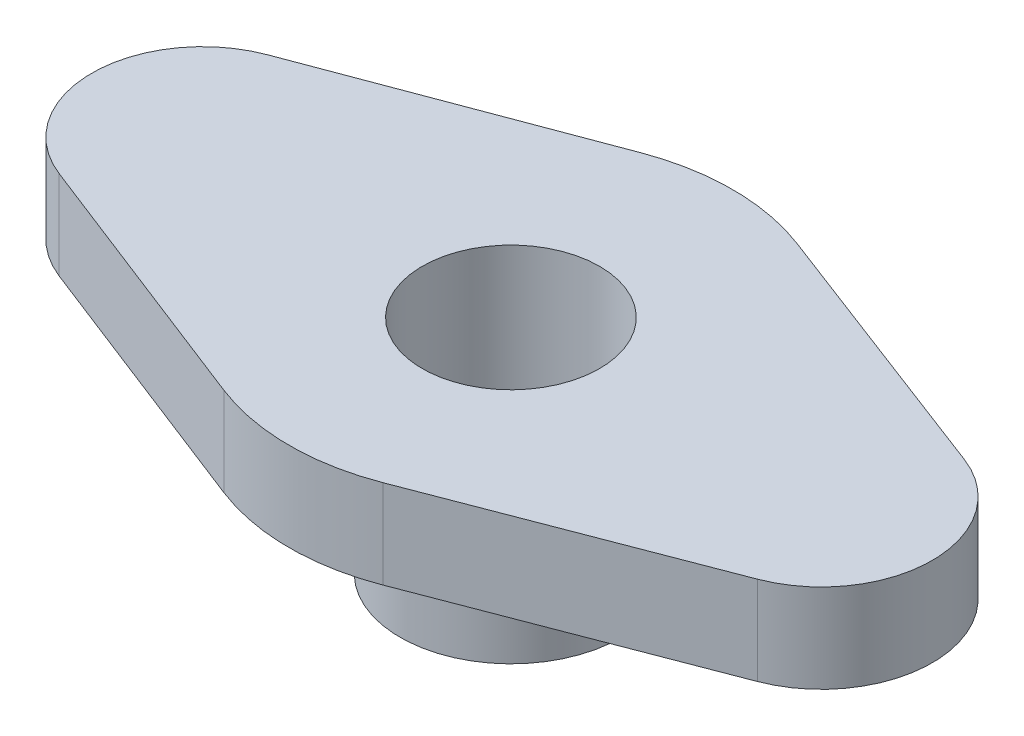
SolidWorks part; units mm, degrees
ref_plane "Plane1" through (0, 0, 0) normal (0, 0, 1) x (1, 0, 0)
ref_plane "Plane2" through (0, 0, 0) normal (0, 1, 0) x (1, 0, 0)
ref_plane "Plane3" through (0, 0, 0) normal (1, 0, 0) x (0, 0, -1)
sketch "Эскиз1" plane through (0, 0, 0) normal (0, -1, 0) x (-1, 0, 0)
  line L0 (-78.9175, 23.3886) -> (-17.835, 46.7109)
  line L1 (17.5567, 46.8163) -> (78.7769, 23.858)
  line L2 (79.077, -22.8436) -> (18.1569, -46.5868)
  line L3 (-17.8793, -46.694) -> (-78.9396, -23.3139)
  arc A0 (-17.8793, -46.694) -> (18.1569, -46.5868) centre (0, 0) ccw
  arc A1 (79.077, -22.8436) -> (78.7769, 23.858) centre (69.9986, 0.4498) ccw
  arc A2 (-78.9175, 23.3886) -> (-78.9396, -23.3139) centre (-70, 0.0331) ccw
  arc A3 (17.5567, 46.8163) -> (-17.835, 46.7109) centre (0, 0) ccw
  dimension "D1" = 100
  dimension "D2" = 50
  dimension "D3" = 50
  dimension "D4" = 70
  dimension "D5" = 70
extrude "Основание-Вытянуть" add sketch "Эскиз1" along normal blind 20
sketch "Sketch1" plane through (0, -20, 0) normal (0, -1, 0) x (1, 0, 0)
  circle A0 centre (0, 0) radius 25
  dimension "D1" = 50
extrude "Boss-Extrude1" add sketch "Sketch1" along normal blind 30
sketch "Sketch2" plane through (0, -50, 0) normal (0, -1, 0) x (1, 0, 0)
  circle A0 centre (0, 0) radius 20
  dimension "D1" = 40
extrude "Cut-Extrude1" cut sketch "Sketch2" against normal through all
equation "\"D1@Sketch2\"=\"D1@Sketch1\"-10"
